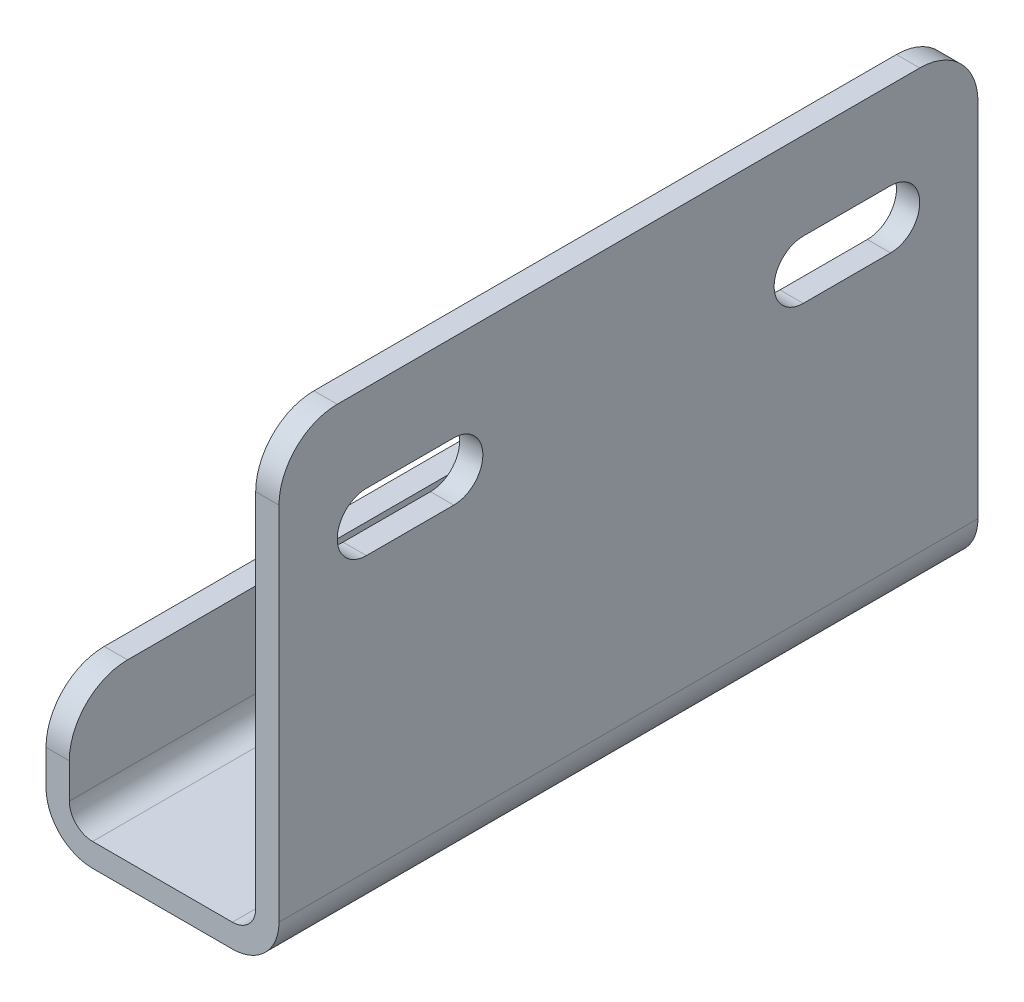
SolidWorks part; units mm, degrees
ref_plane "Front Plane" through (0, 0, 0) normal (0, 0, 1) x (1, 0, 0)
ref_plane "Top Plane" through (0, 0, 0) normal (0, 1, 0) x (1, 0, 0)
ref_plane "Right Plane" through (0, 0, 0) normal (1, 0, 0) x (0, 0, -1)
sketch "Sketch1" plane through (0, 0, 0) normal (0, 0, 1) x (1, 0, 0)
  line L0 (0, 0) -> (0, 48.26)
  line L1 (0, 48.26) -> (2.54, 48.26)
  line L2 (2.54, 48.26) -> (2.54, -2.54)
  line L3 (2.54, -2.54) -> (-22.86, -2.54)
  line L4 (-22.86, -2.54) -> (-22.86, 0)
  line L5 (-20.32, 0) -> (0, 0)
  line L6 (-22.86, 0) -> (-22.86, 12.7)
  line L7 (-22.86, 12.7) -> (-20.32, 12.7)
  line L8 (-20.32, 12.7) -> (-20.32, 0)
  dimension "D1" = 2.54
  dimension "D2" = 2.54
  dimension "D3" = 50.8
  dimension "D4" = 25.4
  dimension "D5" = 2.54
  dimension "D6" = 12.7
extrude "Boss-Extrude1" add sketch "Sketch1" along normal mid plane 76.2
sketch "Sketch2" plane through (0, 0, 0) normal (-1, 0, 0) x (0, 0, 1)
  line L0 (-28.575, 35.56) -> (-19.05, 35.56) construction
  line L1 (-28.575, 38.735) -> (-19.05, 38.735)
  line L2 (-28.575, 32.385) -> (-19.05, 32.385)
  line L3 (19.05, 35.56) -> (28.575, 35.56) construction
  line L4 (19.05, 38.735) -> (28.575, 38.735)
  line L5 (19.05, 32.385) -> (28.575, 32.385)
  line L6 (0, 0) -> (0, 35.56) construction
  line L7 (38.1, 48.26) -> (-38.1, 48.26) construction
  arc A0 (-28.575, 38.735) -> (-28.575, 32.385) centre (-28.575, 35.56) ccw
  arc A1 (-19.05, 32.385) -> (-19.05, 38.735) centre (-19.05, 35.56) ccw
  arc A2 (19.05, 38.735) -> (19.05, 32.385) centre (19.05, 35.56) ccw
  arc A3 (28.575, 32.385) -> (28.575, 38.735) centre (28.575, 35.56) ccw
  point P2 (-23.8125, 35.56)
  point P7 (23.8125, 35.56)
  dimension "D1" = 19.05
  dimension "D2" = 19.05
  dimension "D3" = 6.35
  dimension "D4" = 9.525
  dimension "D5" = 12.7
extrude "Cut-Extrude1" cut sketch "Sketch2" against normal through all both and the other way through all
fillet "Fillet1" radius 6.35 4 edges at (-21.59, 12.7, 38.1) (-21.59, 12.7, -38.1) (1.27, 48.26, -38.1) (1.27, 48.26, 38.1)
fillet "Fillet2" radius 2.54 2 edges at (0, 0, 0) (-20.32, 0, 0)
fillet "Fillet3" radius 5.08 2 edges at (2.54, -2.54, 0) (-22.86, -2.54, 0)
sketch "Schizzo1" plane through (0, 0, 0) normal (0, 1, 0) x (1, 0, 0)
  line L0 (-10.16, 38.1) -> (-10.16, -38.1) construction
  line L1 (-2.54, 38.1) -> (-17.78, 38.1) construction
  line L2 (-2.54, -38.1) -> (-17.78, -38.1) construction
  line L3 (-10.16, 0) -> (-2.54, 0) construction
  line L4 (-2.54, -38.1) -> (-2.54, 38.1) construction
  circle A0 centre (-10.16, 25) radius 1.5
  circle A1 centre (-10.16, -25) radius 1.5
  dimension "D1" = 3
  dimension "D2" = 25
extrude "Taglio-Estrusione1" cut sketch "Schizzo1" against normal blind 10
